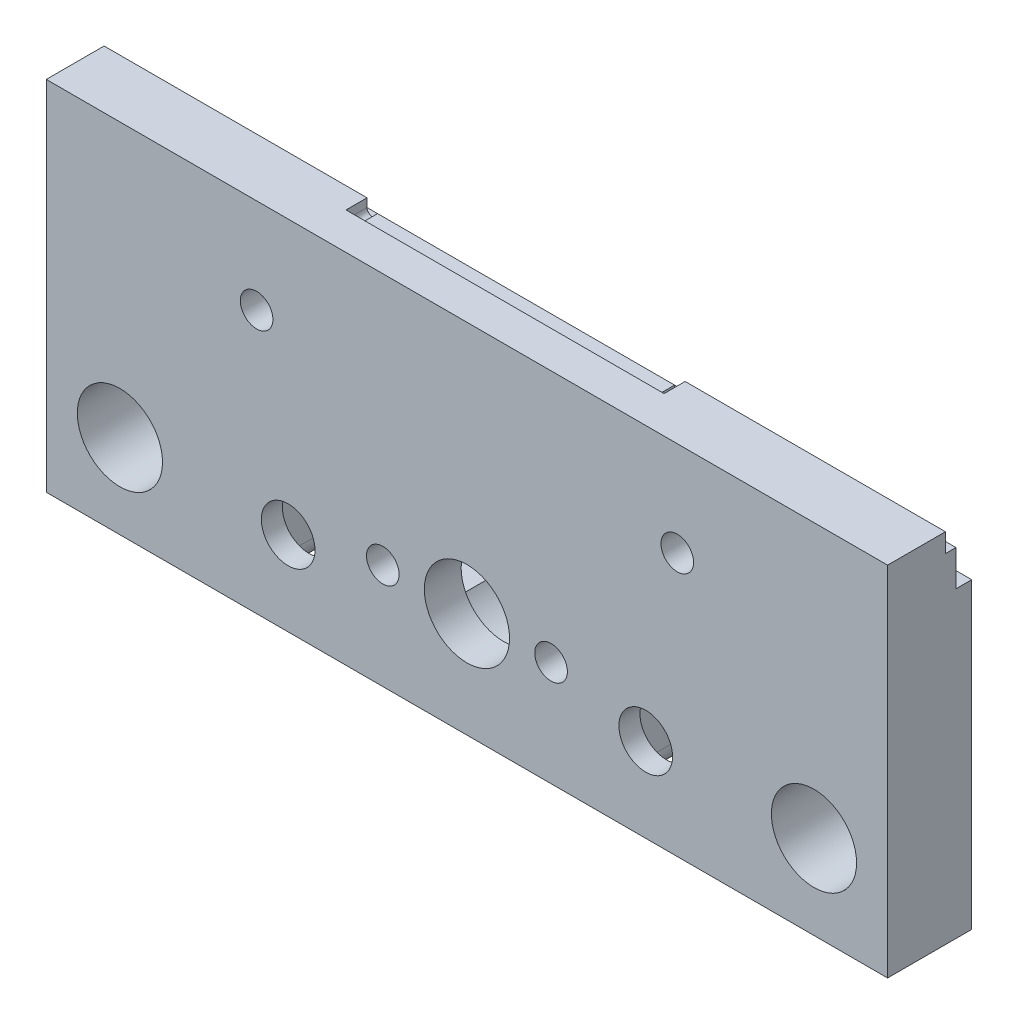
SolidWorks part; units mm, degrees
ref_plane "前视基准面" through (0, 0, 0) normal (0, 0, 1) x (1, 0, 0)
ref_plane "上视基准面" through (0, 0, 0) normal (0, 1, 0) x (1, 0, 0)
ref_plane "右视基准面" through (0, 0, 0) normal (1, 0, 0) x (0, 0, -1)
sketch "前视图草图" plane through (0, 0, 0) normal (0, 0, 1) x (1, 0, 0)
  line L0 (0, 0) -> (44.4821, 0) construction
  line L1 (0, 0) -> (0, 28.3185) construction
sketch "草图2" plane through (0, 0, 0) normal (0, 0, 1) x (1, 0, 0)
  line L0 (0, 0) -> (80, 0)
  line L1 (-200000, 0) -> (200044.4821, 0) construction
  line L2 (80, 0) -> (80, 34)
  line L3 (80, 34) -> (0, 34)
  line L4 (0, -200000) -> (0, 200028.3185) construction
  line L5 (0, 34) -> (0, 0)
  circle A0 centre (7, 8) radius 4.05
  circle A1 centre (40, 10) radius 4.05
  circle A2 centre (73, 8) radius 4.05
  dimension "D3" = 8
  dimension "D5" = 10
  dimension "D9" = 8.1
  dimension "D10" = 8.1
  dimension "D11" = 8.1
  dimension "D1" = 34
  dimension "D2" = 80
  dimension "D4" = 7
  dimension "D6" = 7
  dimension "D7" = 8
  dimension "D8" = 40
extrude "凸台-拉伸1" add sketch "草图2" along normal blind 8
sketch "草图3" plane through (0, 0, 8) normal (0, 0, 1) x (1, 0, 0)
  line L0 (16.088, 8) -> (31.4805, 8) construction
  line L1 (7, 8) -> (7, 16.8386) construction
  line L2 (73, 8) -> (73, 16.5917) construction
  line L4 (-200000, 0) -> (200044.4821, 0) construction
  circle A2 centre (23, 8) radius 2.55
  circle A3 centre (57, 8) radius 2.55
  dimension "D4" = 5.1
  dimension "D5" = 5.1
  dimension "D1" = 8
  dimension "D2" = 16
  dimension "D3" = 16
extrude "切除-拉伸1" cut sketch "草图3" against normal through all
sketch "草图4" plane through (80, 0, 0) normal (1, 0, 0) x (0, 0, -1)
  line L1 (0, -200000) -> (0, 200028.3185) construction
  line L2 (-1.5, 32.2) -> (-2.5, 32.2)
  line L3 (-2.5, 32.2) -> (-2.5, 34)
  line L4 (-8, 34) -> (0, 34) construction
  line L5 (-2.5, 34) -> (0, 34)
  line L6 (-1.5, 32.2) -> (-1.5, 28.8)
  line L7 (-1.5, 28.8) -> (0, 28.8)
  line L8 (0, 28.8) -> (0, 34)
  dimension "D1" = 3.4
  dimension "D2" = 2.5
  dimension "D3" = 1.5
  dimension "D4" = 1.8
extrude "切除-拉伸2" cut sketch "草图4" against normal through all
sketch "草图5" plane through (0, 0, 8) normal (0, 0, 1) x (1, 0, 0)
  line L0 (40, 10) -> (56.5376, 10) construction
  circle A0 centre (40, 10) radius 8 construction
  circle A1 centre (48, 10) radius 1.55
  circle A2 centre (32, 10) radius 1.55
  dimension "D1" = 3.1
  dimension "D2" = 3.1
  dimension "D3" = 16
extrude "切除-拉伸3" cut sketch "草图5" against normal through all
sketch "草图7" plane through (0, 0, 0) normal (0, 0, -1) x (-1, 0, 0)
  line L0 (-40, 12) -> (-40, -8.3696) construction
  line L1 (-23, 10) -> (-23, -2.3368) construction
  line L2 (200000, 0) -> (-200044.4821, 0) construction
  line L6 (-27.05, 10) -> (-27.05, 2.5)
  line L7 (-29.55, 0) -> (-16.45, 0)
  line L8 (-18.95, 2.5) -> (-18.95, 10)
  line L9 (-23, 8) -> (-23, 15.9045) construction
  line L13 (0, -200000) -> (0, 200028.3185) construction
  line L14 (-57, 8) -> (-57, 15.9045) construction
  line L15 (-57, 10) -> (-57, -2.3368) construction
  line L16 (-61.05, 2.5) -> (-61.05, 10)
  line L17 (-50.45, 0) -> (-63.55, 0)
  line L18 (-52.95, 10) -> (-52.95, 2.5)
  arc A1 (-18.95, 10) -> (-27.05, 10) centre (-23, 10) ccw
  arc A4 (-29.55, 0) -> (-27.05, 2.5) centre (-29.55, 2.5) ccw
  arc A5 (-18.95, 2.5) -> (-16.45, 0) centre (-16.45, 2.5) ccw
  arc A7 (-61.05, 2.5) -> (-63.55, 0) centre (-63.55, 2.5) cw
  arc A8 (-50.45, 0) -> (-52.95, 2.5) centre (-50.45, 2.5) cw
  arc A9 (-61.05, 10) -> (-52.95, 10) centre (-57, 10) cw
  dimension "D1" = 40
  dimension "D4" = 8.1
  dimension "D7" = 2.5
  dimension "D8" = 2.5
  dimension "D3" = 10
extrude "切除-拉伸4" cut sketch "草图7" against normal blind 6
sketch "草图8" plane through (0, 0, 0) normal (0, 0, -1) x (-1, 0, 0)
  line L0 (-40, 10) -> (-57.3165, 10) construction
  line L1 (-40, 20) -> (-40, 35.6562) construction
  line L2 (-30.5, 12.85) -> (-49.5, 12.85)
  line L3 (-49.5, 7.15) -> (-30.5, 7.15)
  line L4 (200000, 0) -> (-200044.4821, 0) construction
  arc A0 (-30.5, 7.15) -> (-30.5, 12.85) centre (-30.5, 10) ccw
  arc A1 (-49.5, 12.85) -> (-49.5, 7.15) centre (-49.5, 10) ccw
  dimension "D1" = 5.7
  dimension "D2" = 9.5
  dimension "D3" = 9.5
  dimension "D4" = 10
extrude "切除-拉伸5" cut sketch "草图8" against normal blind 4.5
sketch "草图11" plane through (0, 0, 0) normal (0, 0, -1) x (-1, 0, 0)
  line L0 (0, 34) -> (-80, 34) construction
  line L1 (-80, 0) -> (-80, 28.8) construction
  line L2 (0, -200000) -> (0, 200028.3185) construction
  line L3 (-40, 20) -> (-40, 13.5744) construction
  line L4 (-28.772, 25) -> (-45.9396, 25) construction
  circle A0 centre (-60, 25) radius 1.55
  circle A1 centre (-20, 25) radius 1.55
  point P23 (-40, 20)
  dimension "D1" = 3.1
  dimension "D2" = 3.1
  dimension "D3" = 20
  dimension "D4" = 20
  dimension "D5" = 9
sketch "草图20" plane through (0, 0, 0) normal (0, 0, -1) x (-1, 0, 0)
  circle A0 centre (-40, 10) radius 5.5
  dimension "D1" = 11
extrude "切除-拉伸12" cut sketch "草图20" against normal blind 4.5
extrude "切除-拉伸7" cut sketch "草图11" against normal through all contours A0 | A1
sketch "草图12" plane through (0, 0, 0) normal (0, 0, -1) x (-1, 0, 0)
  line L0 (-62.5, 22.15) -> (-57.5, 22.15)
  line L1 (-57.5, 27.85) -> (-62.5, 27.85)
  line L4 (-80, 0) -> (-80, 28.8) construction
  line L5 (-39.1423, 25) -> (-43.2672, 25) construction
  line L6 (-60, 21) -> (-60, 25.2385) construction
  line L7 (-20, 21) -> (-20, 26.1603) construction
  line L8 (-40, 20) -> (-40, 24.3689) construction
  line L9 (-17.5, 27.85) -> (-22.5, 27.85)
  line L10 (-22.5, 22.15) -> (-17.5, 22.15)
  line L11 (0, -200000) -> (0, 200028.3185) construction
  line L12 (0, 34) -> (-80, 34) construction
  arc A0 (-62.5, 27.85) -> (-62.5, 22.15) centre (-62.5, 25) ccw
  arc A1 (-57.5, 22.15) -> (-57.5, 27.85) centre (-57.5, 25) ccw
  arc A4 (-17.5, 22.15) -> (-17.5, 27.85) centre (-17.5, 25) ccw
  arc A5 (-22.5, 27.85) -> (-22.5, 22.15) centre (-22.5, 25) ccw
  point P16 (-38, 21)
  point P28 (-40, 25)
  point P29 (-40, 25)
  point P30 (0, 0)
  dimension "D2" = 20
  dimension "D3" = 5
  dimension "D4" = 2.5
  dimension "D5" = 20
  dimension "D6" = 9
  dimension "D1" = 2
sketch "草图19" plane through (0, 0, 2.5) normal (0, 0, -1) x (-1, 0, 0)
  line L0 (0, 34) -> (-80, 34) construction
  line L1 (-25, 34) -> (-55.2479, 34)
  line L2 (-25, 34) -> (-25, 33.2)
  line L3 (-26, 33.2) -> (-54.2479, 33.2)
  line L4 (-55.2479, 34) -> (-55.2479, 33.2)
  line L5 (0, -200000) -> (0, 200028.3185) construction
  line L7 (0, 32.2) -> (-80, 32.2) construction
  line L8 (-56.3335, 32.7) -> (-52.9089, 32.7) construction
  line L9 (-55.2479, 1028.5823) -> (-55.2479, 33.2) construction
  line L10 (-25, 1028.5823) -> (-25, 32.7) construction
  line L11 (-55.2479, 32.7) -> (-55.2479, -973.3) construction
  line L12 (-25, 32.7) -> (-25, -973.3) construction
  arc A3 (-55.2479, 33.2) -> (-54.2479, 33.2) centre (-54.7479, 33.2) ccw
  arc A6 (-26, 33.2) -> (-25, 33.2) centre (-25.5, 33.2) ccw
  dimension "D3" = 1
  dimension "D4" = 1
  dimension "D2" = 0.8
  dimension "D1" = 0.5
  dimension "D9" = 25
extrude "切除-拉伸11" cut sketch "草图19" against normal blind 2
